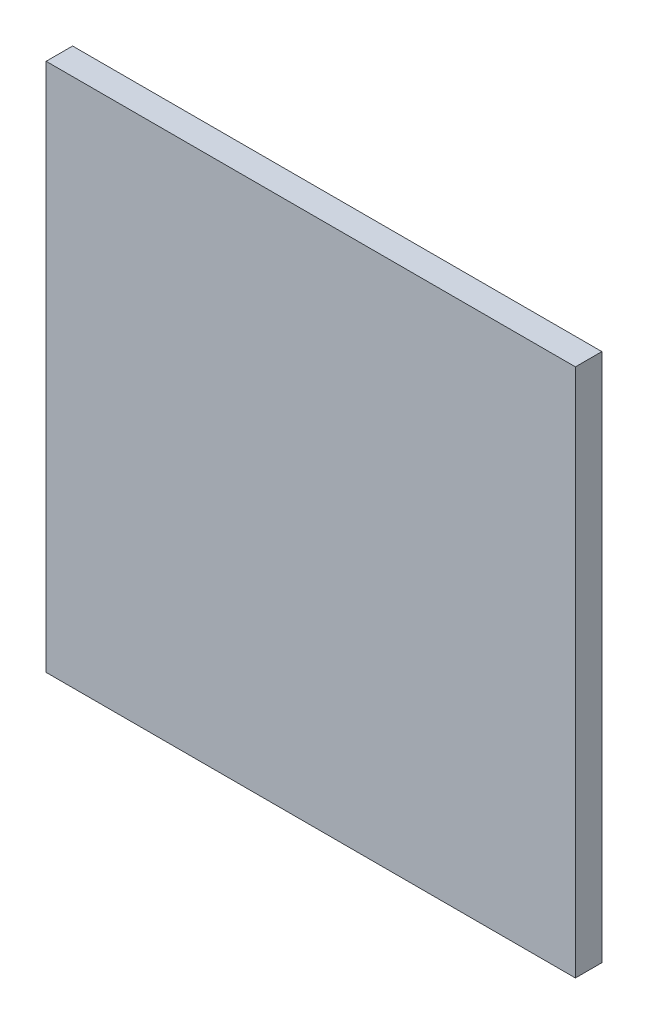
SolidWorks part; units mm, degrees
material "Pin"
ref_plane "Front" through (0, 0, 0) normal (0, 0, 1) x (1, 0, 0)
ref_plane "Top" through (0, 0, 0) normal (0, 1, 0) x (1, 0, 0)
ref_plane "Right" through (0, 0, 0) normal (1, 0, 0) x (0, 0, -1)
sketch "Esquisse1" plane through (0, 0, 0) normal (0, 0, 1) x (1, 0, 0)
  line L1 (-31.75, 31.75) -> (31.75, 31.75)
  line L2 (-31.75, 31.75) -> (-31.75, -31.75)
  line L3 (-31.75, -31.75) -> (31.75, -31.75)
  line L4 (31.75, 31.75) -> (31.75, -31.75)
  line L5 (-31.75, 31.75) -> (31.75, -31.75) construction
  line L6 (-31.75, -31.75) -> (31.75, 31.75) construction
  point P0 (0, 0)
  dimension "D1" = 63.5
  dimension "D2" = 63.5
extrude "Boss.-Extru.1" add sketch "Esquisse1" along normal blind 3.175
sketch "Esquisse2" plane through (0, 0, 3.175) normal (0, 0, 1) x (1, 0, 0)
  text T0 "<b>GRO 66</b>" font "Britannic Bold" height 9.525
  point P1 (-24.6697, -2.3409)
  point P2 (0, 0)
  dimension "D1" = 4.7625
  dimension "D2" = 24.638
